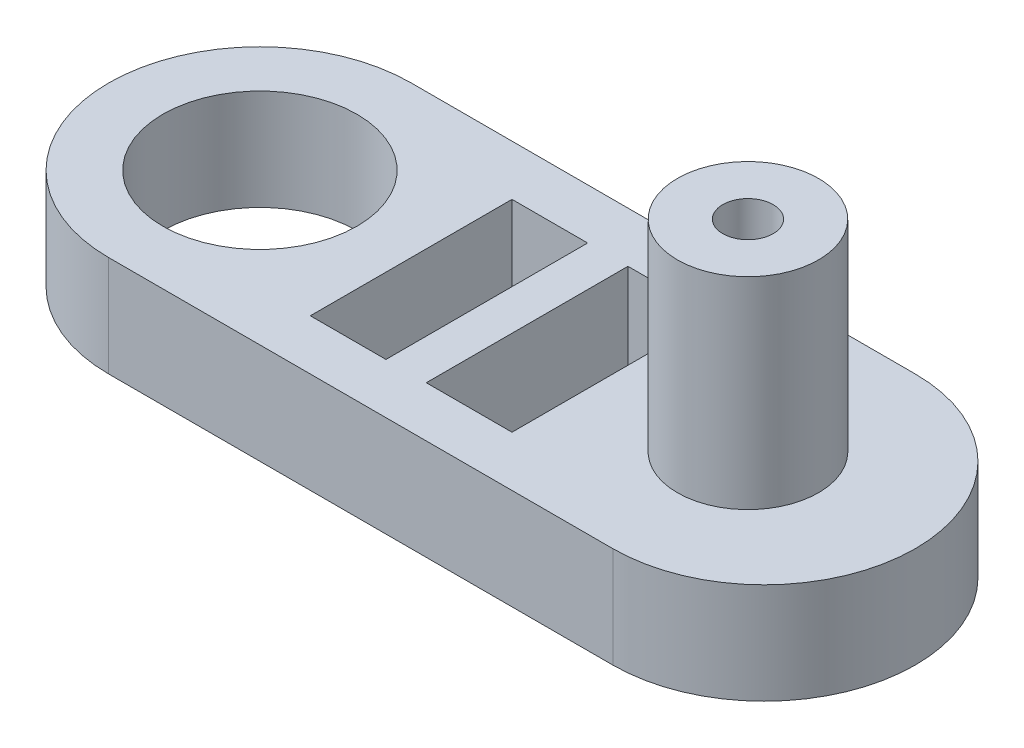
SolidWorks part; units mm, degrees
ref_plane "Front Plane" through (0, 0, 0) normal (0, 0, 1) x (1, 0, 0)
ref_plane "Top Plane" through (0, 0, 0) normal (0, 1, 0) x (1, 0, 0)
ref_plane "Right Plane" through (0, 0, 0) normal (1, 0, 0) x (0, 0, -1)
sketch "Sketch1" plane through (0, 0, 0) normal (0, 1, 0) x (1, 0, 0)
  line L0 (-55, 0) -> (55, 0) construction
  line L1 (-48.4, 0) -> (1.6, 0) construction
  line L2 (-48.4, 15) -> (1.6, 15)
  line L3 (-48.4, -15) -> (1.6, -15)
  circle A0 centre (-48.4, 0) radius 9.625
  arc A2 (-48.4, 15) -> (-48.4, -15) centre (-48.4, 0) ccw
  arc A3 (1.6, -15) -> (1.6, 15) centre (1.6, 0) ccw
  point P6 (-23.4, 0)
  dimension "D2" = 19.25
  dimension "D4" = 15
  dimension "D1" = 50
extrude "Boss-Extrude1" add sketch "Sketch1" along normal blind 10
sketch "Sketch2" plane through (0, 10, 0) normal (0, 1, 0) x (1, 0, 0)
  line L1 (-33.4, 10) -> (-13.4, 10)
  line L2 (-33.4, 10) -> (-33.4, -10)
  line L3 (-33.4, -10) -> (-13.4, -10)
  line L4 (-13.4, 10) -> (-13.4, -10)
  circle A0 centre (-48.4, 0) radius 9.625 construction
  arc A1 (-48.4, 15) -> (-48.4, -15) centre (-48.4, 0) ccw construction
  dimension "D1" = 20
  dimension "D2" = 20
  dimension "D3" = 10
  dimension "D4" = 15
extrude "Cut-Extrude1" cut sketch "Sketch2" against normal through all
sketch "Sketch4" plane through (0, 0, -10) normal (0, 0, 1) x (1, 0, 0)
  line L0 (-13.4, 10) -> (-33.4, 10) construction
  line L1 (-25.9, 10) -> (-21.9, 10)
  line L2 (-25.9, 10) -> (-25.9, 0)
  line L3 (-25.9, 0) -> (-21.9, 0)
  line L4 (-21.9, 10) -> (-21.9, 0)
  line L5 (-13.4, 0) -> (-33.4, 0) construction
  line L6 (-33.4, 0) -> (-33.4, 10) construction
  dimension "D1" = 7.5
  dimension "D2" = 4
extrude "Boss-Extrude2" add sketch "Sketch4" along normal up to next
sketch "Sketch5" plane through (0, 10, 0) normal (0, 1, 0) x (1, 0, 0)
  circle A0 centre (0, 0) radius 7
extrude "Boss-Extrude3" add sketch "Sketch5" along normal blind 20
sketch "Sketch8" plane through (0, 30, 0) normal (0, 1, 0) x (1, 0, 0)
  circle A0 centre (0, 0) radius 2.5
extrude "Cut-Extrude2" cut sketch "Sketch8" against normal blind 10
